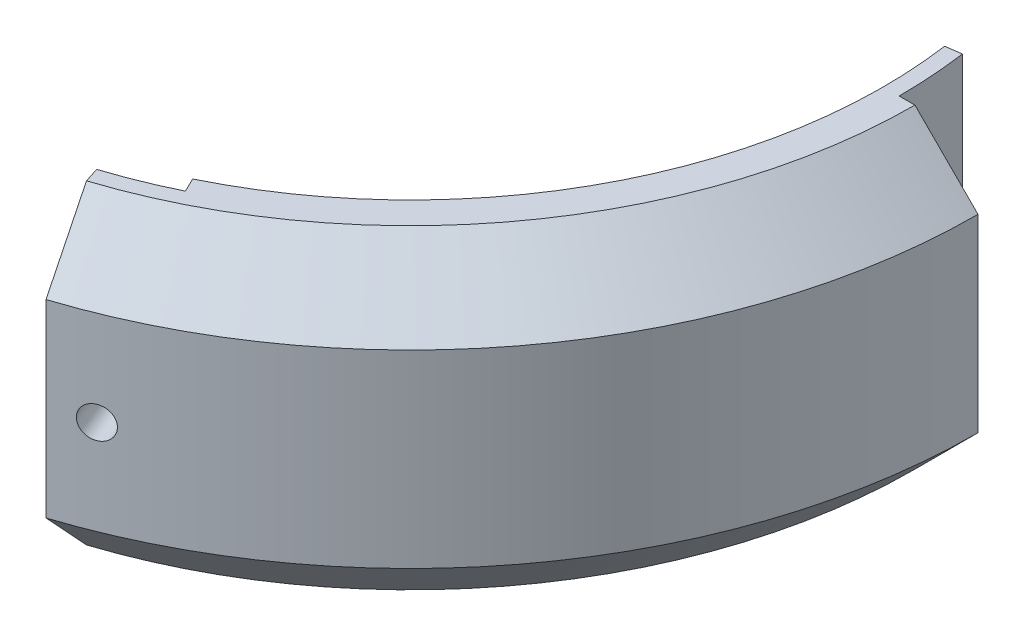
SolidWorks part; units mm, degrees
material "Rubber"
ref_plane "Front Plane" through (0, 0, 0) normal (0, 0, 1) x (1, 0, 0)
ref_plane "Top Plane" through (0, 0, 0) normal (0, 1, 0) x (1, 0, 0)
ref_plane "Right Plane" through (0, 0, 0) normal (1, 0, 0) x (0, 0, -1)
ref_axis "Axis1" through (0, 54.031, 0) along (0, -1, 0)
sketch "Sketch1" plane through (0, 0, 0) normal (0, 0, 1) x (1, 0, 0)
  line L0 (0, 0) -> (75, 0) construction
  line L1 (75, 25) -> (75, 12.5)
  line L2 (70, 7.5) -> (70, -7.5)
  line L3 (70, 7.5) -> (75, 12.5)
  line L4 (70, -7.5) -> (75, -12.5)
  line L5 (80, 27.5279) -> (80, -29.466) construction
  line L6 (90, 15) -> (90, -15)
  line L7 (75, -25) -> (80, -25)
  line L8 (80, -25) -> (90, -15)
  line L9 (75, 25) -> (80, 25)
  line L10 (80, 25) -> (90, 15)
  line L11 (75, -12.5) -> (75, -25)
  point P6 (75, 0)
  point P9 (65, 0)
  point P13 (0, 0)
  point P14 (70, 0)
  dimension "D1" = 75
  dimension "D2" = 25
  dimension "D3" = 5
  dimension "D4" = 15
  dimension "D5" = 5
  dimension "D6" = 10
  dimension "D7" = 25
  dimension "D8" = 45
  dimension "D9" = 45
revolve "Revolve1" add sketch "Sketch1" angle 72 about axis through (0, 54.031, 0) along (0, -1, 0)
sketch "Sketch2" plane through (0, 0, 0) normal (0, 1, 0) x (1, 0, 0)
  line L0 (0, 0) -> (108.7122, 0) construction
  line L1 (0, 0) -> (50.9767, -104.5177)
  line L3 (74.2701, 10.438) -> (89.1241, 12.5256)
  line L4 (75, 0) -> (90, 0)
  line L5 (21.6312, -66.574) -> (23.1763, -71.3292)
  line L6 (23.1763, -71.3292) -> (23.9488, -73.7069)
  arc A0 (23.1763, -71.3292) -> (74.2701, 10.438) centre (0, 0) ccw construction
  arc A1 (23.1763, -71.3292) -> (74.2701, 10.438) centre (0, 0) ccw construction
  arc A2 (27.8115, -85.5951) -> (89.1241, 12.5256) centre (0, 0) ccw construction
  arc A3 (27.8115, -85.5951) -> (89.1241, 12.5256) centre (0, 0) ccw
  arc A4 (21.6312, -66.574) -> (69.3188, 9.7421) centre (0, 0) ccw construction
  arc A5 (21.6312, -66.574) -> (69.3188, 9.7421) centre (0, 0) ccw
  arc A6 (23.9488, -73.7069) -> (76.7458, 10.7859) centre (0, 0) ccw
  dimension "D1" = 64
  dimension "D2" = 2.5
extrude "Cut-Extrude2" cut sketch "Sketch2" against normal through all both and the other way through all contours A6 L4 A3 L3 | L6 A6 L1 A5 L5
sketch "Sketch3" plane through (0, 0, 0) normal (0, 1, 0) x (1, 0, 0)
  line L0 (0, 0) -> (53.703, 0) construction
  line L1 (0, 0) -> (19.2536, -47.6544) construction
  dimension "D1" = 68
ref_plane "Plane1" through (0, 0, 0) normal (0.3746, 0, 0.9272) x (0.9272, 0, -0.3746)
sketch "Sketch5" plane through (0, 0, 0) normal (0.3746, 0, 0.9272) x (0.9272, 0, -0.3746)
  circle A0 centre (0, 0) radius 2.5
  dimension "D1" = 5
extrude "Cut-Extrude3" cut sketch "Sketch5" along normal through all
pattern_circular "CirPattern1" count 2 over 72 about axis through (0, 54.031, 0) along (0, -1, 0) of "Cut-Extrude3"
equation "\"D1@Sketch2\"=72-8"
